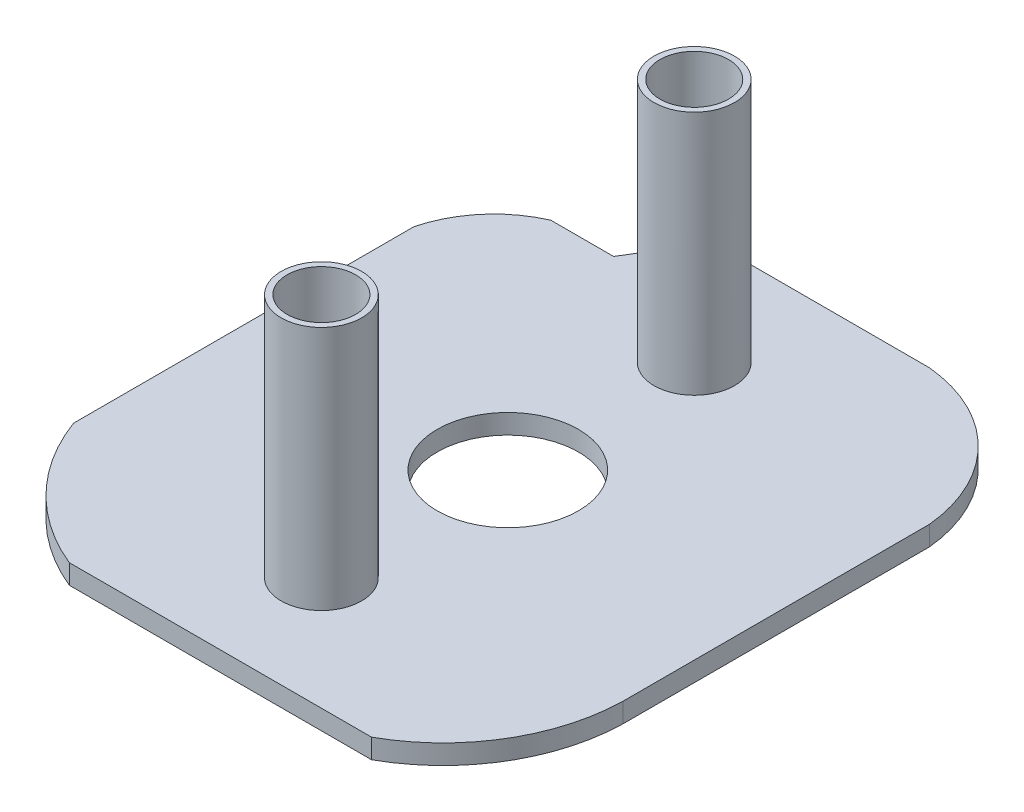
SolidWorks part; units mm, degrees
ref_plane "Front Plane" through (0, 0, 0) normal (0, 0, 1) x (1, 0, 0)
ref_plane "Top Plane" through (0, 0, 0) normal (0, 1, 0) x (1, 0, 0)
ref_plane "Right Plane" through (0, 0, 0) normal (1, 0, 0) x (0, 0, -1)
sketch "Sketch3" plane through (0, 0, 0) normal (0, 1, 0) x (1, 0, 0)
  line L1 (-131.4, -152.64) -> (131.4, -152.64)
  line L2 (-131.4, -152.64) -> (-131.4, 152.64)
  line L3 (-131.4, 152.64) -> (131.4, 152.64)
  line L4 (131.4, -152.64) -> (131.4, 152.64)
  line L5 (-131.4, -152.64) -> (131.4, 152.64) construction
  line L6 (-131.4, 152.64) -> (131.4, -152.64) construction
  point P0 (0, 0)
extrude "Boss-Extrude3" add sketch "Sketch3" along normal blind 10
sketch "Sketch4" plane through (0, 10, 0) normal (0, 1, 0) x (1, 0, 0)
  line L0 (0, 0) -> (0, 36) construction
  line L1 (-131.4, -152.64) -> (-131.4, -90) construction
  line L2 (-131.4, 152.64) -> (-131.4, -152.64) construction
  line L3 (-131.4, -152.64) -> (-70.92, -152.64) construction
  line L4 (-131.4, -152.64) -> (131.4, -152.64) construction
  line L5 (-131.4, -90) -> (-131.4, -152.64)
  line L6 (-131.4, -152.64) -> (-70.92, -152.64)
  line L7 (131.4, -152.64) -> (131.4, -72.72) construction
  line L8 (131.4, -152.64) -> (131.4, 152.64) construction
  line L9 (-131.4, -152.64) -> (83.16, -152.64) construction
  line L10 (83.16, -152.64) -> (131.4, -152.64)
  line L11 (131.4, -152.64) -> (131.4, -72.72)
  line L12 (131.4, -152.64) -> (131.4, 83.52) construction
  line L13 (-131.4, 152.64) -> (-131.4, 121.2871) construction
  line L14 (-99.3727, 121.2871) -> (-67.3455, 121.2871)
  line L15 (131.4, 83.52) -> (131.4, 152.64)
  line L16 (131.4, 152.64) -> (62.28, 152.64)
  line L17 (-131.4, 152.64) -> (-78.12, 152.64) construction
  line L18 (-131.4, 121.2871) -> (-67.3455, 121.2871) construction
  line L19 (-67.3455, 121.2871) -> (-48.1593, 152.64) construction
  line L20 (131.4, 152.64) -> (-131.4, 152.64) construction
  line L21 (131.4, 83.52) -> (-131.4, 83.52) construction
  line L22 (-67.3455, 121.2871) -> (-48.1593, 152.64)
  line L23 (-48.1593, 152.64) -> (-131.4, 152.64)
  line L24 (-131.4, 152.64) -> (-131.4, 83.52)
  arc A0 (-70.92, -152.64) -> (-131.4, -90) centre (-30.0903, -52.7009) cw
  arc A1 (83.16, -152.64) -> (131.4, -72.72) centre (37.7004, -70.6815) ccw
  arc A2 (62.28, 152.64) -> (131.4, 83.52) centre (55.08, 76.32) cw
  arc A3 (-131.4, 83.52) -> (-99.3727, 121.2871) centre (-76.5887, 69.5023) cw
extrude "Cut-Extrude1" cut sketch "Sketch4" against normal through all both and the other way through all
sketch "Sketch5" plane through (0, 10, 0) normal (0, 1, 0) x (1, 0, 0)
  line L0 (0, 0) -> (0, 36) construction
  circle A0 centre (0, 0) radius 36
extrude "Cut-Extrude2" cut sketch "Sketch5" against normal through all both and the other way through all
sketch "Sketch6" plane through (0, 10, 0) normal (0, 1, 0) x (1, 0, 0)
  line L0 (0, 153.7787) -> (0, 152.64) construction
  line L1 (62.28, 152.64) -> (-48.1593, 152.64) construction
  line L2 (0, 152.64) -> (0, 95.04) construction
  line L3 (0, 0) -> (-176.4283, 0) construction
  circle A0 centre (0, 95.04) radius 20.52
  circle A1 centre (0, -95.04) radius 20.52
extrude "Boss-Extrude4" add sketch "Sketch6" along normal blind 125
sketch "Sketch7" plane through (0, 135, 0) normal (0, 1, 0) x (1, 0, 0)
  line L0 (0, 0) -> (71.0102, 0) construction
  circle A0 centre (0, 95.04) radius 17.5
  circle A1 centre (0, -95.04) radius 17.5
extrude "Cut-Extrude3" cut sketch "Sketch7" against normal through all both and the other way through all
